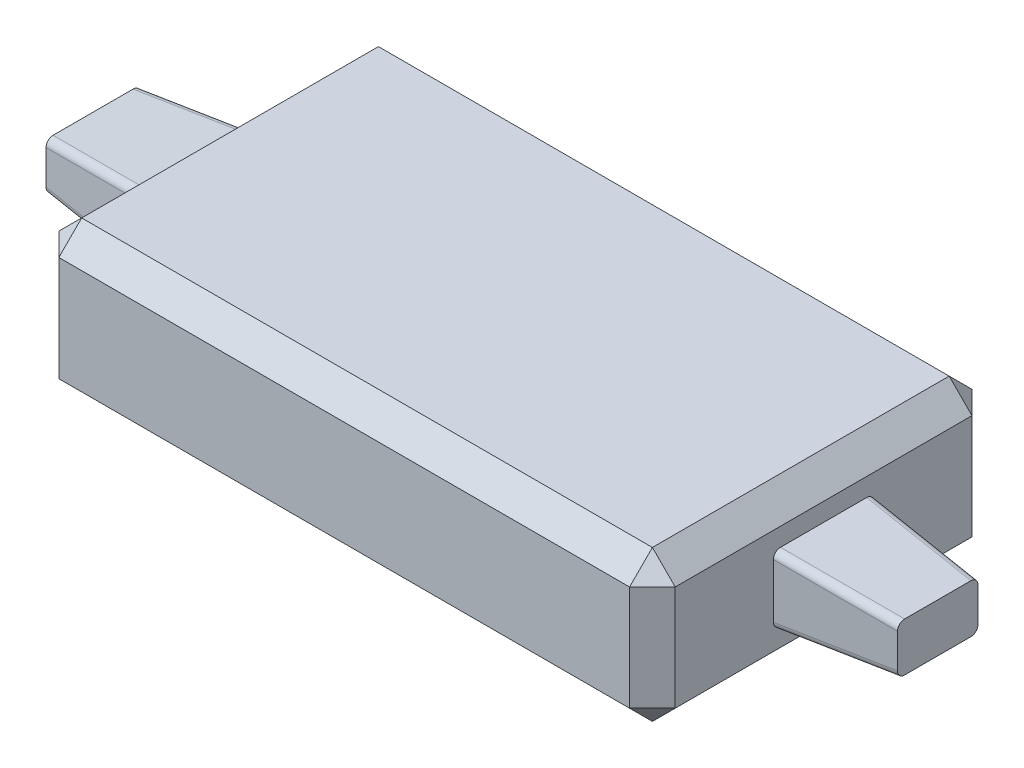
SolidWorks part; units mm, degrees
ref_plane "Front Plane" through (0, 0, 0) normal (0, 0, 1) x (1, 0, 0)
ref_plane "Top Plane" through (0, 0, 0) normal (0, 1, 0) x (1, 0, 0)
ref_plane "Right Plane" through (0, 0, 0) normal (1, 0, 0) x (0, 0, -1)
sketch "Sketch1" plane through (0, 0, 0) normal (0, 1, 0) x (1, 0, 0)
  line L1 (-17.145, -9.525) -> (17.145, -9.525)
  line L2 (-17.145, -9.525) -> (-17.145, 9.525)
  line L3 (-17.145, 9.525) -> (17.145, 9.525)
  line L4 (17.145, -9.525) -> (17.145, 9.525)
  line L5 (-17.145, -9.525) -> (17.145, 9.525) construction
  line L6 (-17.145, 9.525) -> (17.145, -9.525) construction
  point P0 (0, 0)
  dimension "D1" = 34.29
  dimension "D2" = 19.05
extrude "Boss-Extrude1" add sketch "Sketch1" along normal blind 8.382
sketch "Sketch2" plane through (0, 0, 0) normal (0, -1, 0) x (-1, 0, 0)
  line L0 (-17.145, 0) -> (-5.715, 0) construction
  line L1 (-17.145, -9.525) -> (-17.145, 9.525) construction
  line L2 (-5.715, 0) -> (5.715, 0) construction
  line L3 (5.715, 0) -> (17.145, 0) construction
  line L4 (17.145, 9.525) -> (17.145, -9.525) construction
  circle A0 centre (5.715, 0) radius 2.286
  circle A1 centre (-5.715, 0) radius 2.286
  dimension "D1" = 4.572
  dimension "D2" = 4.572
extrude "Boss-Extrude2" add sketch "Sketch2" along normal blind 1.27
sketch "Sketch3" plane through (-17.145, 0, 0) normal (-1, 0, 0) x (0, 0, 1)
  line L0 (0, 8.382) -> (0, 4.191) construction
  line L1 (-3.175, 2.286) -> (3.175, 2.286)
  line L2 (-3.175, 2.286) -> (-3.175, 6.096)
  line L3 (-3.175, 6.096) -> (3.175, 6.096)
  line L4 (3.175, 2.286) -> (3.175, 6.096)
  line L5 (-3.175, 2.286) -> (3.175, 6.096) construction
  line L6 (-3.175, 6.096) -> (3.175, 2.286) construction
  line L7 (-9.525, 8.382) -> (9.525, 8.382) construction
  line L8 (0, 4.191) -> (0, 0) construction
  line L9 (-9.525, 0) -> (9.525, 0) construction
  point P0 (0, 4.191)
  dimension "D1" = 6.35
  dimension "D2" = 3.81
extrude "Boss-Extrude3" add sketch "Sketch3" along normal blind 6.35 draft 5 separate body
sketch "Sketch4" plane through (17.145, 0, 0) normal (1, 0, 0) x (0, 0, -1)
  line L0 (0, 8.382) -> (0, 4.191) construction
  line L1 (-2.794, 6.096) -> (2.794, 6.096)
  line L2 (-2.794, 6.096) -> (-2.794, 2.286)
  line L3 (-2.794, 2.286) -> (2.794, 2.286)
  line L4 (2.794, 6.096) -> (2.794, 2.286)
  line L5 (-2.794, 6.096) -> (2.794, 2.286) construction
  line L6 (-2.794, 2.286) -> (2.794, 6.096) construction
  line L7 (-9.525, 8.382) -> (9.525, 8.382) construction
  line L8 (0, 4.191) -> (0, 0) construction
  line L9 (-9.525, 0) -> (9.525, 0) construction
  point P0 (0, 4.191)
  dimension "D1" = 5.588
  dimension "D2" = 3.81
extrude "Boss-Extrude4" add sketch "Sketch4" along normal blind 6.35 draft 5 separate body
chamfer "Chamfer1" distance 1.27 angle 45 12 edges at (-17.145, 0, 0) (-17.145, 4.191, -9.525) (0, 0, -9.525) (-17.145, 4.191, 9.525) (0, 0, 9.525) (17.145, 4.191, 9.525) (17.145, 0, 0) (17.145, 4.191, -9.525) (0, 8.382, 9.525) (-17.145, 8.382, 0) (0, 8.382, -9.525) (17.145, 8.382, 0)
fillet "Fillet1" radius 0.3969 4 edges at (20.32, 2.5638, -2.5162) (20.32, 2.5638, 2.5162) (20.32, 5.8182, 2.5162) (20.32, 5.8182, -2.5162)
fillet "Fillet2" radius 0.3969 4 edges at (-20.32, 2.5638, -2.8972) (-20.32, 2.5638, 2.8972) (-20.32, 5.8182, -2.8972) (-20.32, 5.8182, 2.8972)
